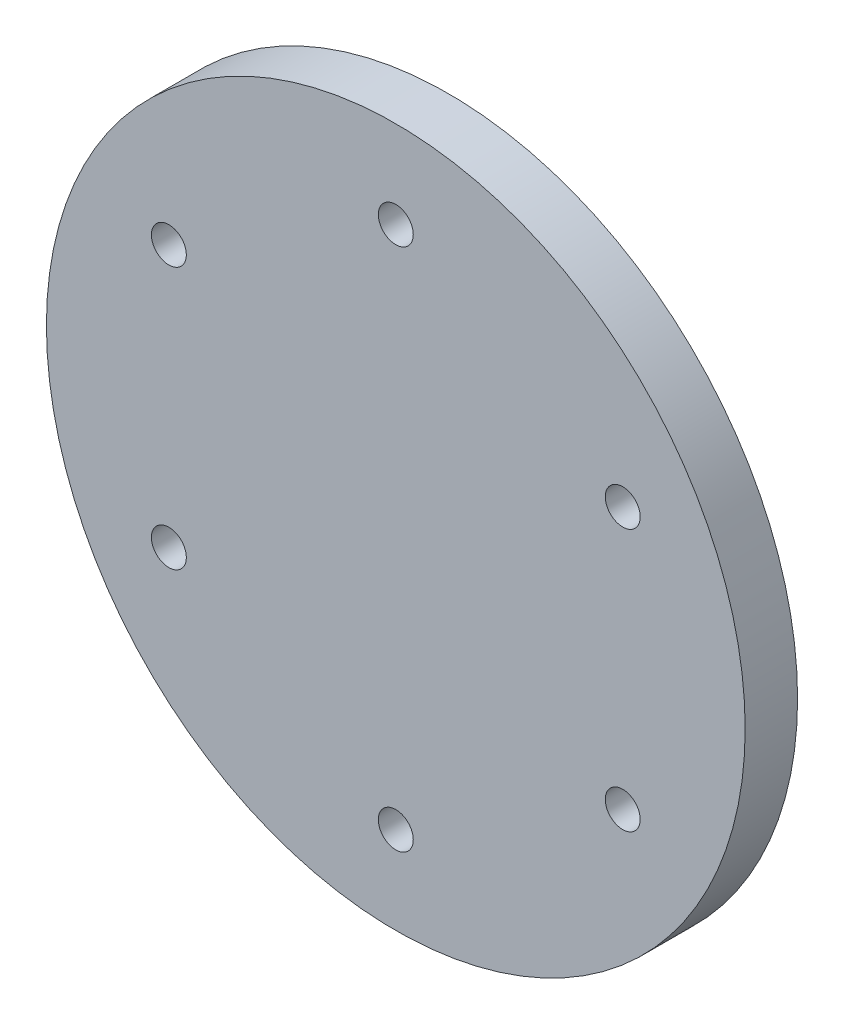
SolidWorks part; units mm, degrees
ref_plane "Front Plane" through (0, 0, 0) normal (0, 0, 1) x (1, 0, 0)
ref_plane "Top Plane" through (0, 0, 0) normal (0, 1, 0) x (1, 0, 0)
ref_plane "Right Plane" through (0, 0, 0) normal (1, 0, 0) x (0, 0, -1)
sketch "Sketch1" plane through (0, 0, 0) normal (0, 0, 1) x (1, 0, 0)
  circle A0 centre (0, 0) radius 40
  point P0 (0, 0)
  point P6 (0, 0)
  dimension "D1" = 80
extrude "Boss-Extrude1" add sketch "Sketch1" along normal blind 6
sketch "Sketch2" plane through (0, 0, 0) normal (0, 0, 1) x (1, 0, 0)
  circle A0 centre (0, 0) radius 30 construction
  circle A1 centre (0, 30) radius 2
  circle A2 centre (0, 0) radius 30 construction
  circle A3 centre (25.9808, 15) radius 2
  circle A4 centre (0, 0) radius 30 construction
  circle A5 centre (25.9808, -15) radius 2
  circle A6 centre (0, 0) radius 30 construction
  circle A7 centre (0, -30) radius 2
  circle A8 centre (0, 0) radius 30 construction
  circle A9 centre (-25.9808, -15) radius 2
  circle A10 centre (0, 0) radius 30 construction
  circle A11 centre (-25.9808, 15) radius 2
  point P23 (0, 0)
  dimension "D1" = 60
  dimension "D2" = 4
  dimension "D3" = 6
extrude "Cut-Extrude1" cut sketch "Sketch2" along normal through all
